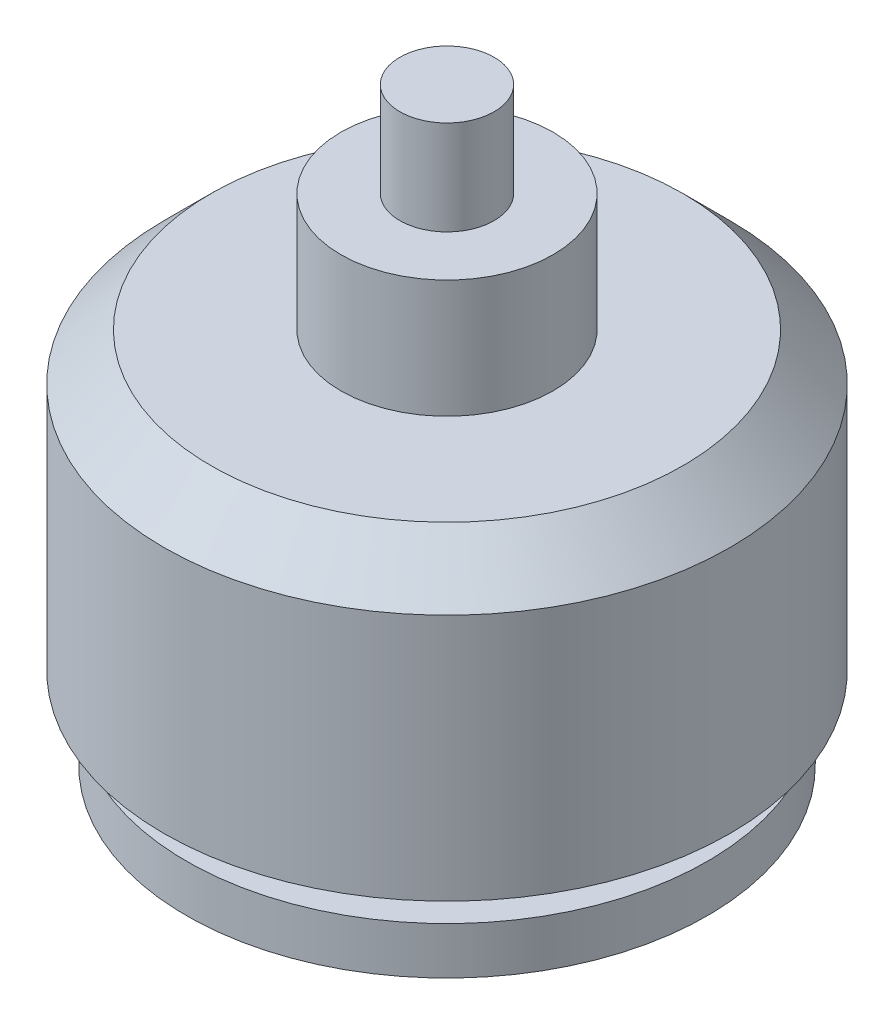
SolidWorks part; units mm, degrees
ref_plane "Front Plane" through (0, 0, 0) normal (0, 0, 1) x (1, 0, 0)
ref_plane "Top Plane" through (0, 0, 0) normal (0, 1, 0) x (1, 0, 0)
ref_plane "Right Plane" through (0, 0, 0) normal (1, 0, 0) x (0, 0, -1)
sketch "Sketch1" plane through (0, 0, 0) normal (0, 0, 1) x (1, 0, 0)
  line L0 (0, 0) -> (22.08, 0)
  line L1 (22.08, 0) -> (22.08, 4)
  line L2 (22.08, 4) -> (16.8, 4)
  line L3 (16.8, 4) -> (16.8, 7)
  line L4 (16.8, 7) -> (24, 7)
  line L5 (24, 7) -> (24, 28)
  line L6 (24, 28) -> (20, 32)
  line L7 (20, 32) -> (9, 32)
  line L8 (9, 32) -> (9, 42)
  line L9 (9, 42) -> (4, 42)
  line L10 (4, 42) -> (4, 50)
  line L11 (4, 50) -> (0, 50)
  line L12 (0, 50) -> (0, 0)
  line L13 (0, -10) -> (0, 1000) construction
revolve "Revolve1" add sketch "Sketch1" angle 360 about L13
